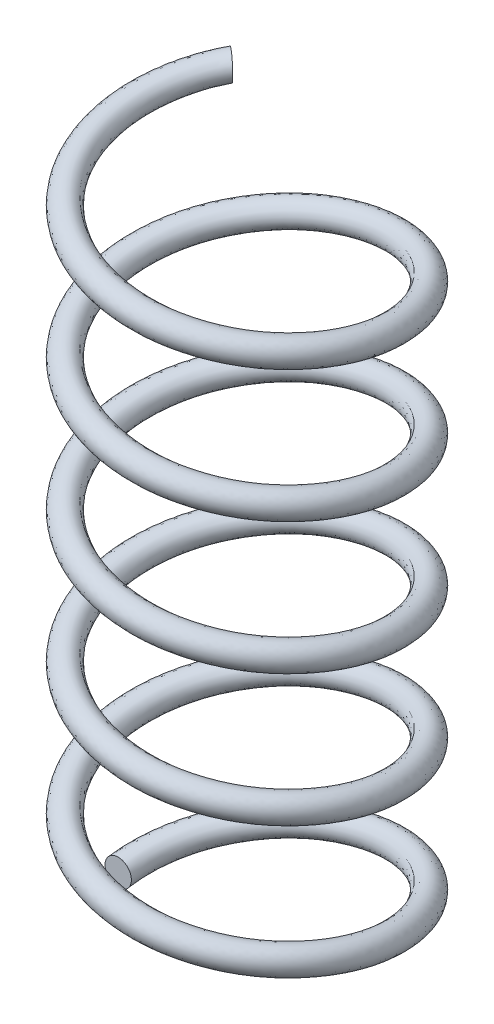
SolidWorks part; units mm, degrees
ref_plane "Front Plane" through (0, 0, 0) normal (0, 0, 1) x (1, 0, 0)
ref_plane "Top Plane" through (0, 0, 0) normal (0, 1, 0) x (1, 0, 0)
ref_plane "Right Plane" through (0, 0, 0) normal (1, 0, 0) x (0, 0, -1)
sketch "Sketch2" plane through (0, 0, 0) normal (0, 1, 0) x (1, 0, 0)
  circle A0 centre (0, 0) radius 2.2
  dimension "D1" = 4.4
curve "Helix/Spiral1" pitch 2.25 height 11.5 turns 5.1111
sketch "Sketch3" plane through (0, 0, 0) normal (0, 0, 1) x (1, 0, 0)
  line L0 (-2.2, 0) -> (0, 0) construction
  circle A0 centre (-2.2, 0) radius 0.225
  dimension "D1" = 0.45
  dimension "D2" = 2.2
sweep "Sweep1" add profiles "Sketch3" path "Helix/Spiral1"
